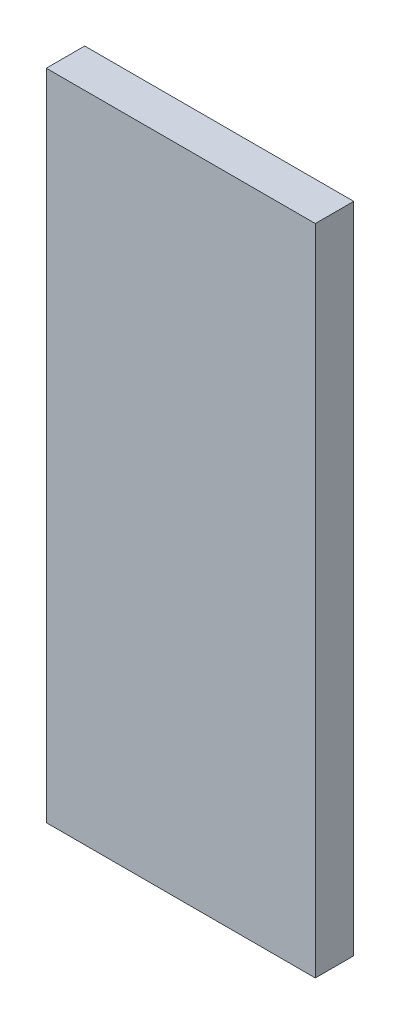
SolidWorks part; units mm, degrees
ref_plane "Front Plane" through (0, 0, 0) normal (0, 0, 1) x (1, 0, 0)
ref_plane "Top Plane" through (0, 0, 0) normal (0, 1, 0) x (1, 0, 0)
ref_plane "Right Plane" through (0, 0, 0) normal (1, 0, 0) x (0, 0, -1)
sketch "Sketch1" plane through (0, 0, 0) normal (0, 0, 1) x (1, 0, 0)
  line L1 (0, 0) -> (350, 0)
  line L2 (0, 0) -> (0, 850)
  line L3 (0, 850) -> (350, 850)
  line L4 (350, 0) -> (350, 850)
  dimension "D1" = 350
  dimension "D2" = 850
extrude "Reference_only" add sketch "Sketch1" along normal blind 50
